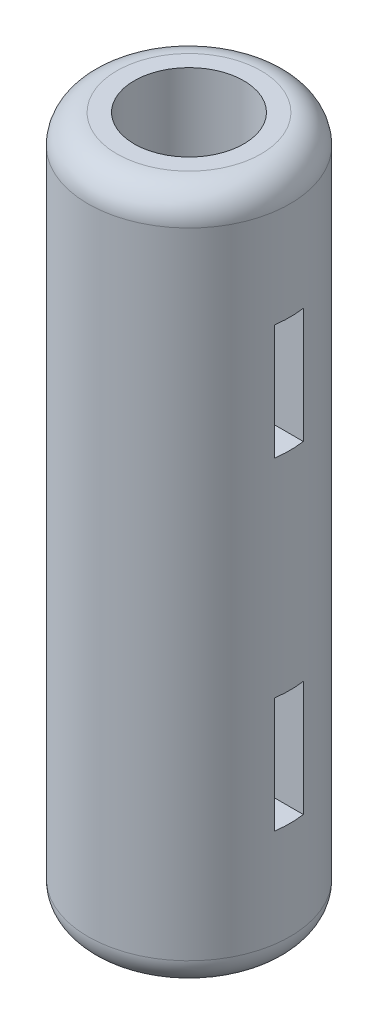
SolidWorks part; units mm, degrees
ref_plane "Front Plane" through (0, 0, 0) normal (0, 0, 1) x (1, 0, 0)
ref_plane "Top Plane" through (0, 0, 0) normal (0, 1, 0) x (1, 0, 0)
ref_plane "Right Plane" through (0, 0, 0) normal (1, 0, 0) x (0, 0, -1)
sketch "Sketch3" plane through (0, 0, 0) normal (0, 1, 0) x (1, 0, 0)
  circle A0 centre (0, 0) radius 19
  circle A1 centre (0, 0) radius 35
extrude "Boss-Extrude2" add sketch "Sketch3" along normal blind 240
sketch "Sketch5" plane through (0, 0, 0) normal (1, 0, 0) x (0, 0, -1)
  line L2 (0, 240) -> (0, 0)
  line L3 (19, 240) -> (-19, 240) construction
  line L4 (0, 240) -> (0, 176)
  line L6 (-5, 156) -> (5, 156)
  line L7 (-5, 156) -> (-5, 196)
  line L8 (-5, 196) -> (5, 196)
  line L9 (5, 156) -> (5, 196)
  line L10 (-5, 156) -> (5, 196) construction
  line L11 (-5, 196) -> (5, 156) construction
extrude "Cut-Extrude2" cut sketch "Sketch5" against normal through all and the other way through all contours L9 L8 L7 L6
sketch "Sketch6" plane through (0, 0, 0) normal (1, 0, 0) x (0, 0, -1)
  line L2 (-5, 84) -> (5, 84)
  line L3 (-5, 84) -> (-5, 44)
  line L4 (-5, 44) -> (5, 44)
  line L5 (5, 84) -> (5, 44)
  line L6 (-5, 84) -> (5, 44) construction
  line L7 (-5, 44) -> (5, 84) construction
extrude "Cut-Extrude3" cut sketch "Sketch6" against normal through all and the other way through all
fillet "Fillet2" radius 10 1 edges at (0, 240, 35)
fillet "Fillet3" radius 10 1 edges at (0, 0, 35)
